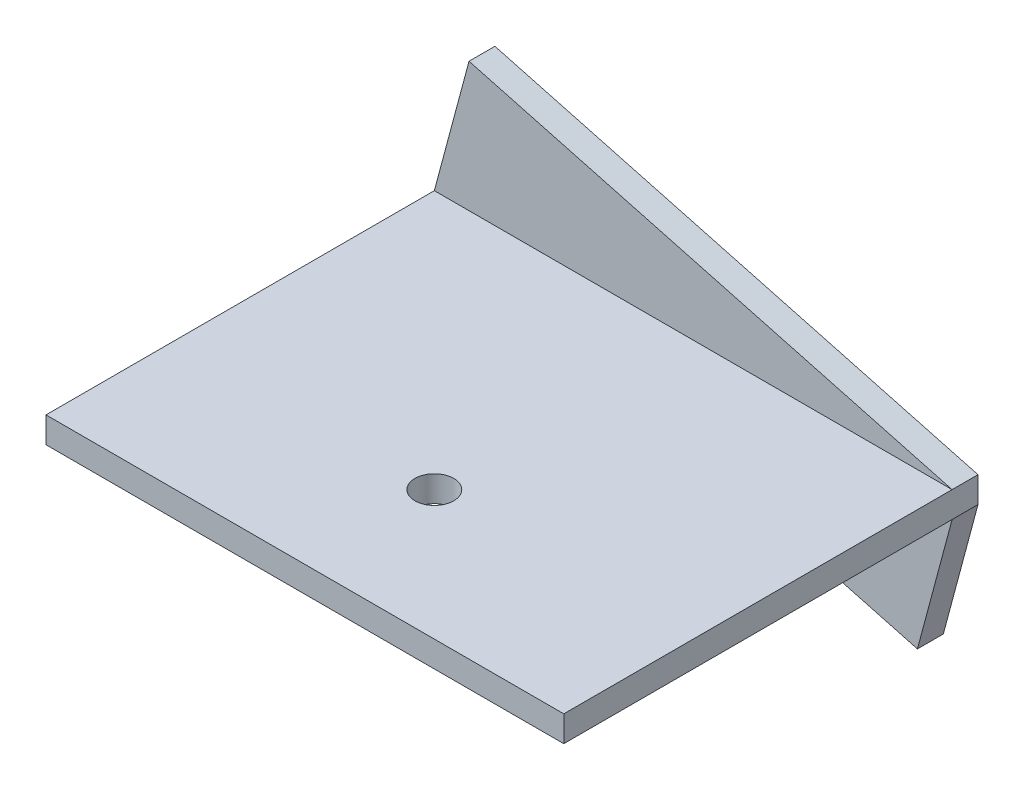
SolidWorks part; units mm, degrees
ref_plane "Front Plane" through (0, 0, 0) normal (0, 0, 1) x (1, 0, 0)
ref_plane "Top Plane" through (0, 0, 0) normal (0, 1, 0) x (1, 0, 0)
ref_plane "Right Plane" through (0, 0, 0) normal (1, 0, 0) x (0, 0, -1)
sketch "Sketch1" plane through (0, 0, 0) normal (0, 1, 0) x (1, 0, 0)
  line L1 (-40, 30) -> (40, 30)
  line L2 (-40, 30) -> (-40, -30)
  line L3 (-40, -30) -> (40, -30)
  line L4 (40, 30) -> (40, -30)
  line L5 (-40, 30) -> (40, -30) construction
  line L6 (-40, -30) -> (40, 30) construction
  point P0 (0, 0)
  dimension "D1" = 60
  dimension "D2" = 80
extrude "Boss-Extrude1" add sketch "Sketch1" along normal blind 4
sketch "Sketch2" plane through (0, 4, 0) normal (0, 1, 0) x (1, 0, 0)
  line L0 (-40, 30) -> (-40, -30) construction
  line L1 (-40, -30) -> (40, -30) construction
  circle A0 centre (0, -10) radius 3
  dimension "D1" = 6
  dimension "D2" = 40
  dimension "D3" = 20
extrude "Cut-Extrude1" cut sketch "Sketch2" against normal blind 4
sketch "Sketch8" plane through (0, 0, -30) normal (0, 0, -1) x (-1, 0, 0)
  line L0 (-40, 4) -> (37.2741, 24.7055)
  line L5 (-40, 0) -> (40, 0)
  line L6 (40, 0) -> (40, 4)
  line L7 (40, 4) -> (-40, 4)
  line L8 (-40, 4) -> (-40, 0)
  line L11 (40, 4) -> (-40, 4)
  arc A0 (40, 4) -> (37.2741, 24.7055) centre (-40, 4) ccw
  dimension "D1" = 0
extrude "Boss-Extrude4" add sketch "Sketch8" along normal blind 4 separate body
sketch "Sketch9" plane through (0, 4, 0) normal (0, -1, 0) x (1, 0, 0)
  line L1 (40, -30) -> (-40, -30)
  line L2 (40, -30) -> (40, -34)
  line L3 (40, -34) -> (-40, -34)
  line L4 (-40, -30) -> (-40, -34)
extrude "Boss-Extrude5" add sketch "Sketch9" along normal blind 54
sketch "Sketch10" plane through (0, 0, -30) normal (0, 0, 1) x (1, 0, 0)
  line L0 (-40, 4) -> (-34.641, 24)
  line L1 (-37.2741, 24.7055) -> (40, 4) construction
  line L2 (-34.641, 24) -> (-48.0429, 27.591)
  line L3 (-48.0429, 27.591) -> (-40, 4)
extrude "Cut-Extrude5" cut sketch "Sketch10" against normal blind 54
sketch "Sketch11" plane through (0, 0, -30) normal (0, 0, 1) x (1, 0, 0)
  line L0 (40, 0) -> (26.6025, -50)
  line L1 (40, -50) -> (40, 0) construction
  line L2 (40, -50) -> (-40, -50) construction
  line L3 (26.6025, -50) -> (60.4063, -52.4748)
  line L4 (60.4063, -52.4748) -> (40, 0)
extrude "Cut-Extrude6" cut sketch "Sketch11" against normal blind 54
sketch "Sketch12" plane through (0, 0, -30) normal (0, 0, 1) x (1, 0, 0)
  line L0 (-40, 0) -> (34.641, -20)
  line L1 (40, 0) -> (26.6025, -50) construction
  line L2 (34.641, -20) -> (30.3736, -54.2287)
  line L3 (30.3736, -54.2287) -> (-68.4227, -51.1859)
  line L4 (-68.4227, -51.1859) -> (-40, 0)
extrude "Cut-Extrude7" cut sketch "Sketch12" against normal blind 54
